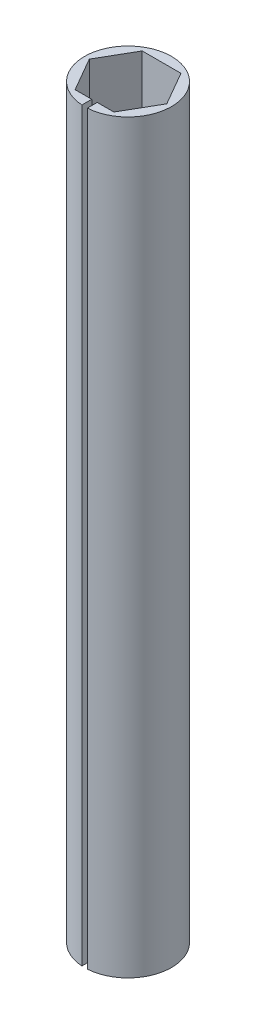
SolidWorks part; units mm, degrees
ref_plane "Front Plane" through (0, 0, 0) normal (0, 0, 1) x (1, 0, 0)
ref_plane "Top Plane" through (0, 0, 0) normal (0, 1, 0) x (1, 0, 0)
ref_plane "Right Plane" through (0, 0, 0) normal (1, 0, 0) x (0, 0, -1)
sketch "Sketch1" plane through (0, 0, 0) normal (0, 1, 0) x (1, 0, 0)
  line L1 (3.9595, -6.858) -> (7.9189, 0)
  line L2 (7.9189, 0) -> (3.9595, 6.858)
  line L3 (3.9595, 6.858) -> (-3.9595, 6.858)
  line L4 (-3.9595, 6.858) -> (-7.9189, 0)
  line L5 (-7.9189, 0) -> (-3.9595, -6.858)
  line L6 (-3.9595, -6.858) -> (3.9595, -6.858)
  circle A0 centre (0, 0) radius 8.89
  circle A1 centre (0, 0) radius 6.858 construction
  dimension "D1" = 17.78
  dimension "D2" = 13.716
extrude "Boss-Extrude1" add sketch "Sketch1" along normal blind 152.4
sketch "Sketch2" plane through (0, 0, 0) normal (0, -1, 0) x (-1, 0, 0)
  line L1 (0.5566, -4.0468) -> (-0.5566, -4.0468)
  line L2 (0.5566, -4.0468) -> (0.5566, -12.6611)
  line L3 (0.5566, -12.6611) -> (-0.5566, -12.6611)
  line L4 (-0.5566, -4.0468) -> (-0.5566, -12.6611)
  line L5 (0.5566, -4.0468) -> (-0.5566, -12.6611) construction
  line L6 (0.5566, -12.6611) -> (-0.5566, -4.0468) construction
  point P0 (0, -8.3539)
  point P5 (0, 0)
extrude "Cut-Extrude1" cut sketch "Sketch2" against normal through all
